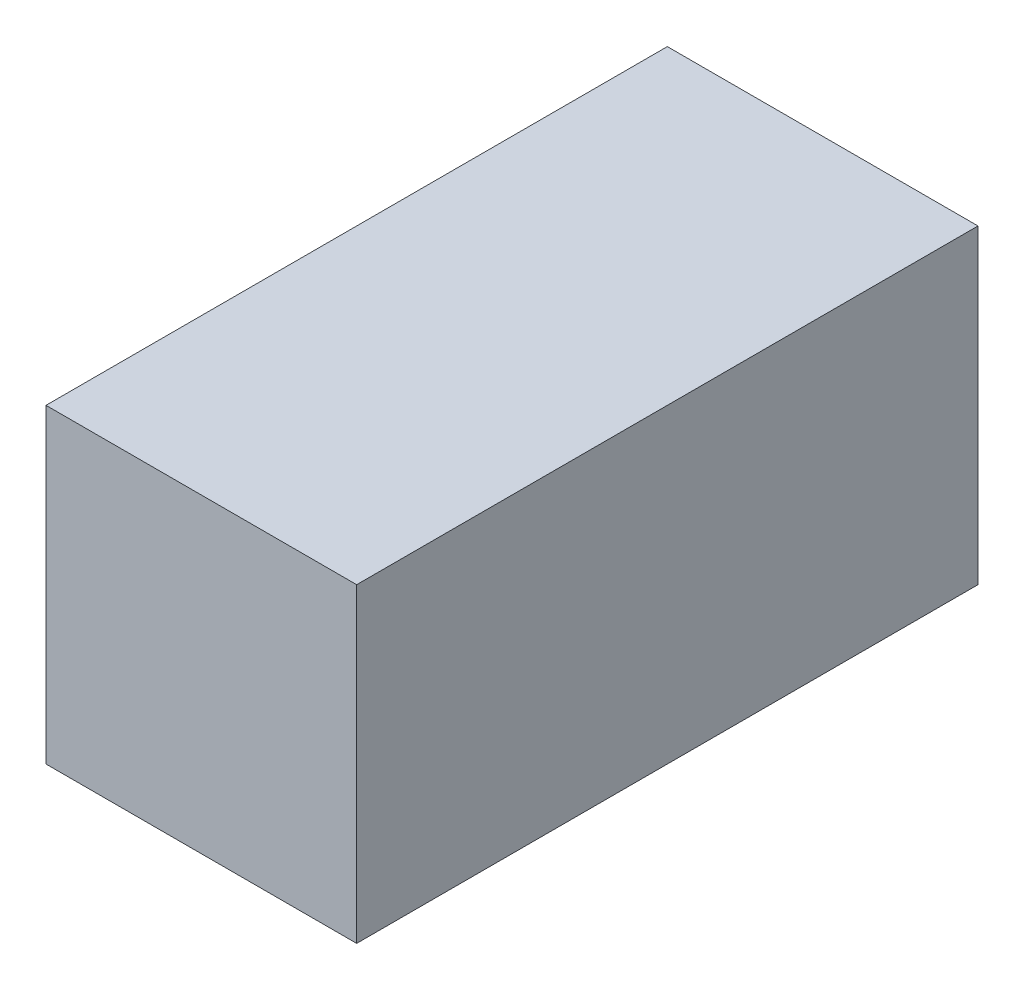
SolidWorks part; units mm, degrees
ref_plane "Plan de face" through (0, 0, 0) normal (0, 0, 1) x (1, 0, 0)
ref_plane "Plan de dessus" through (0, 0, 0) normal (0, 1, 0) x (1, 0, 0)
ref_plane "Plan de droite" through (0, 0, 0) normal (1, 0, 0) x (0, 0, -1)
sketch "Esquisse1" plane through (0, 0, 0) normal (0, 0, 1) x (1, 0, 0)
  line L1 (-50, -50) -> (50, -50)
  line L2 (-50, -50) -> (-50, 50)
  line L3 (-50, 50) -> (50, 50)
  line L4 (50, -50) -> (50, 50)
  line L5 (-50, -50) -> (50, 50) construction
  line L6 (-50, 50) -> (50, -50) construction
  point P0 (0, 0)
  dimension "D1" = 100
  dimension "D2" = 100
extrude "Boss.-Extru.1" add sketch "Esquisse1" along normal blind 200
sketch "Esquisse2" plane through (0, -50, 0) normal (0, -1, 0) x (1, 0, 0)
  line L0 (40, 190) -> (-40, 190)
  line L1 (-40, 190) -> (-40, 10)
  line L2 (-40, 10) -> (40, 10)
  line L3 (40, 10) -> (40, 190)
  line L4 (-50, 0) -> (50, 0)
  line L5 (50, 0) -> (50, 200)
  line L6 (50, 200) -> (-50, 200)
  line L7 (-50, 200) -> (-50, 0)
  line L8 (-50, 0) -> (50, 0)
  line L9 (50, 0) -> (50, 200)
  line L10 (50, 200) -> (-50, 200)
  line L11 (-50, 200) -> (-50, 0)
  dimension "D1" = 0
  dimension "D2" = 10
extrude "Enlèv. mat.-Extru.1" cut sketch "Esquisse2" against normal blind 15 contours L0 L1 L2 L3
sketch "Esquisse3" plane through (-40, 0, 0) normal (1, 0, 0) x (0, 0, -1)
  line L0 (-185, -50) -> (-185, -35)
  line L1 (-200, -50) -> (0, -50) construction
  line L2 (-185, -35) -> (-170, -35)
  line L3 (-170, -35) -> (-170, -50)
  line L4 (-170, -50) -> (-185, -50)
  line L5 (-190, -35) -> (-190, -50) construction
  dimension "D1" = 15
  dimension "D2" = 15
  dimension "D3" = 5
extrude "Boss.-Extru.2" add sketch "Esquisse3" along normal blind 80
pattern_linear "Répétition linéaire1" count 6 spacing 20 along (0, 0, -1) of "Boss.-Extru.2"
sketch "Esquisse4" plane through (0, -50, 0) normal (0, -1, 0) x (1, 0, 0)
  line L0 (-50, 200) -> (-50, 0) construction
  line L1 (-40, 180) -> (10, 180)
  line L2 (-40, 180) -> (-40, 175)
  line L3 (-40, 175) -> (10, 175)
  line L4 (10, 180) -> (10, 175)
  line L5 (-40, 180) -> (10, 175) construction
  line L6 (-40, 175) -> (10, 180) construction
  line L7 (40, 185) -> (-40, 185) construction
  line L8 (40, 185) -> (-40, 185) construction
  line L9 (18, 179) -> (25, 179)
  line L10 (18, 179) -> (18, 183)
  line L11 (18, 183) -> (25, 183)
  line L12 (25, 179) -> (25, 183)
  line L13 (18, 179) -> (25, 183) construction
  line L14 (18, 183) -> (25, 179) construction
  line L15 (18, 172) -> (25, 172)
  line L16 (18, 172) -> (18, 176)
  line L17 (18, 176) -> (25, 176)
  line L18 (25, 172) -> (25, 176)
  line L19 (18, 172) -> (25, 176) construction
  line L20 (18, 176) -> (25, 172) construction
  line L21 (40, 170) -> (-40, 170) construction
  line L22 (50, 200) -> (50, 0) construction
  point P0 (-15, 177.5)
  point P9 (21.5, 181)
  point P14 (21.5, 174)
  point P19 (20.9787, 180.6512)
  dimension "D1" = 10
  dimension "D2" = 5
  dimension "D3" = 5
  dimension "D4" = 50
  dimension "D5" = 4
  dimension "D6" = 7
  dimension "D7" = 4
  dimension "D8" = 7
  dimension "D9" = 2
  dimension "D10" = 2
  dimension "D11" = 25
extrude "Enlèv. mat.-Extru.2" cut sketch "Esquisse4" against normal blind 2
pattern_linear "Répétition linéaire2" count 6 spacing 20 along (0, 0, -1) of "Enlèv. mat.-Extru.2"
sketch "Esquisse5" plane through (0, 0, 70) normal (0, 0, -1) x (-1, 0, 0)
  line L0 (35, -50) -> (35, -35)
  line L1 (50, -50) -> (-50, -50) construction
  line L2 (35, -35) -> (10, -35)
  line L3 (10, -35) -> (10, -50)
  line L4 (10, -50) -> (35, -50)
  line L5 (40, -50) -> (40, -35) construction
  dimension "D1" = 15
  dimension "D2" = 25
  dimension "D3" = 5
extrude "Boss.-Extru.3" add sketch "Esquisse5" along normal blind 60
sketch "Esquisse6" plane through (-10, 0, 0) normal (1, 0, 0) x (0, 0, -1)
  line L0 (-65, -50) -> (-65, -35)
  line L1 (-200, -50) -> (0, -50) construction
  line L2 (-65, -35) -> (-50, -35)
  line L3 (-50, -35) -> (-50, -50)
  line L4 (-50, -50) -> (-65, -50)
  line L5 (-70, -35) -> (-70, -50) construction
  dimension "D1" = 15
  dimension "D2" = 15
  dimension "D3" = 5
extrude "Boss.-Extru.4" add sketch "Esquisse6" along normal blind 50
pattern_linear "Répétition linéaire3" count 2 spacing 30 along (0, 0, -1) of "Boss.-Extru.4"
sketch "Esquisse7" plane through (0, -50, 0) normal (0, -1, 0) x (1, 0, 0)
  line L0 (-50, 0) -> (50, 0) construction
  line L1 (-29, 10) -> (-23, 10)
  line L2 (-29, 10) -> (-29, 55)
  line L3 (-29, 55) -> (-23, 55)
  line L4 (-23, 10) -> (-23, 55)
  line L5 (-29, 10) -> (-23, 55) construction
  line L6 (-29, 55) -> (-23, 10) construction
  line L7 (-35, 10) -> (-35, 70) construction
  line L8 (50, 200) -> (50, 0) construction
  line L9 (-10, 55) -> (25, 55)
  line L10 (-10, 55) -> (-10, 60)
  line L11 (-10, 60) -> (25, 60)
  line L12 (25, 55) -> (25, 60)
  line L13 (-10, 55) -> (25, 60) construction
  line L14 (-10, 60) -> (25, 55) construction
  line L15 (-10, 25) -> (25, 25)
  line L16 (-10, 25) -> (-10, 30)
  line L17 (-10, 30) -> (25, 30)
  line L18 (25, 25) -> (25, 30)
  line L19 (-10, 25) -> (25, 30) construction
  line L20 (-10, 30) -> (25, 25) construction
  line L21 (40, 35) -> (-10, 35) construction
  line L22 (40, 65) -> (-10, 65) construction
  point P0 (-26, 32.5)
  point P5 (7.5, 27.5)
  point P13 (7.5, 57.5)
  dimension "D1" = 45
  dimension "D2" = 6
  dimension "D3" = 10
  dimension "D4" = 6
  dimension "D5" = 35
  dimension "D6" = 5
  dimension "D7" = 25
  dimension "D8" = 25
  dimension "D9" = 5
  dimension "D10" = 5
extrude "Enlèv. mat.-Extru.3" cut sketch "Esquisse7" against normal blind 3
